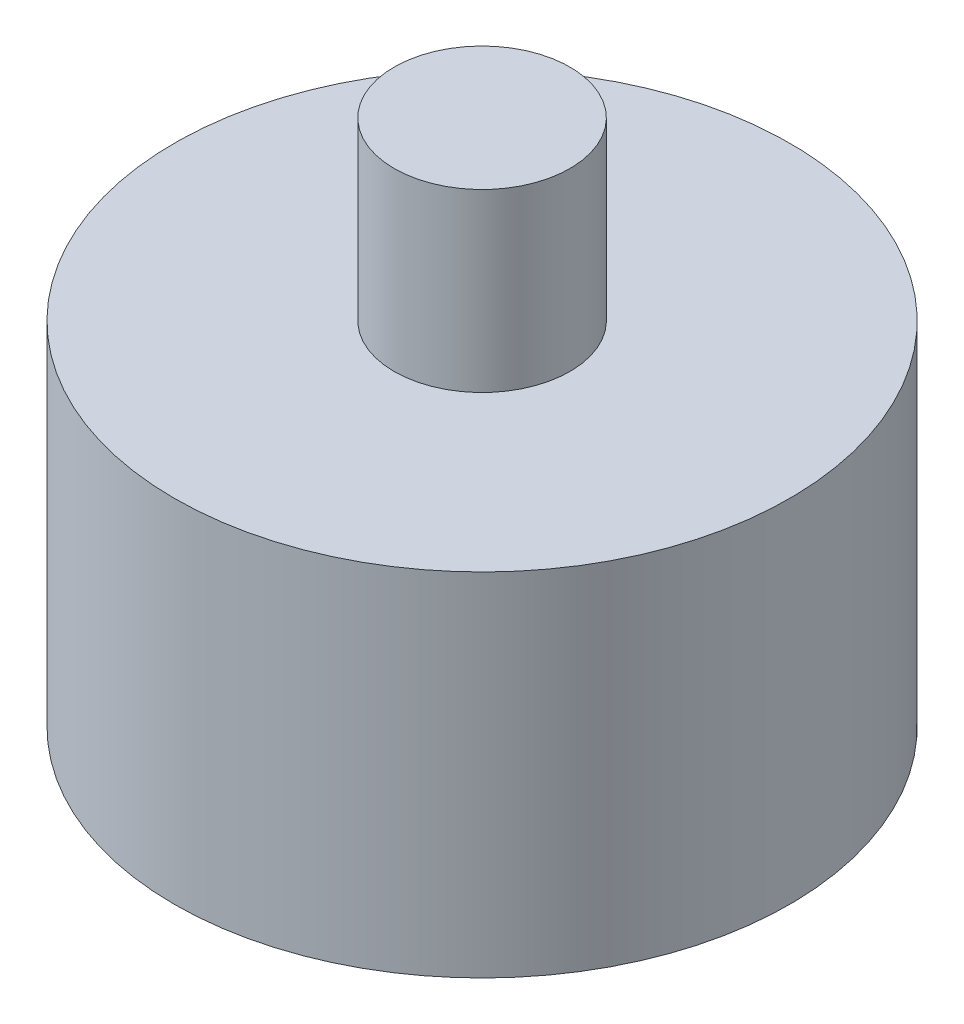
SolidWorks part; units mm, degrees
ref_plane "Front Plane" through (0, 0, 0) normal (0, 0, 1) x (1, 0, 0)
ref_plane "Top Plane" through (0, 0, 0) normal (0, 1, 0) x (1, 0, 0)
ref_plane "Right Plane" through (0, 0, 0) normal (1, 0, 0) x (0, 0, -1)
sketch "Sketch1" plane through (0, 0, 0) normal (0, 1, 0) x (1, 0, 0)
  circle A0 centre (0, 0) radius 17.5
  dimension "D1" = 35
extrude "Boss-Extrude1" add sketch "Sketch1" along normal blind 20
sketch "Sketch2" plane through (0, 20, 0) normal (0, 1, 0) x (1, 0, 0)
  circle A0 centre (0, 0) radius 5
  dimension "D1" = 10
extrude "Boss-Extrude2" add sketch "Sketch2" along normal blind 10
